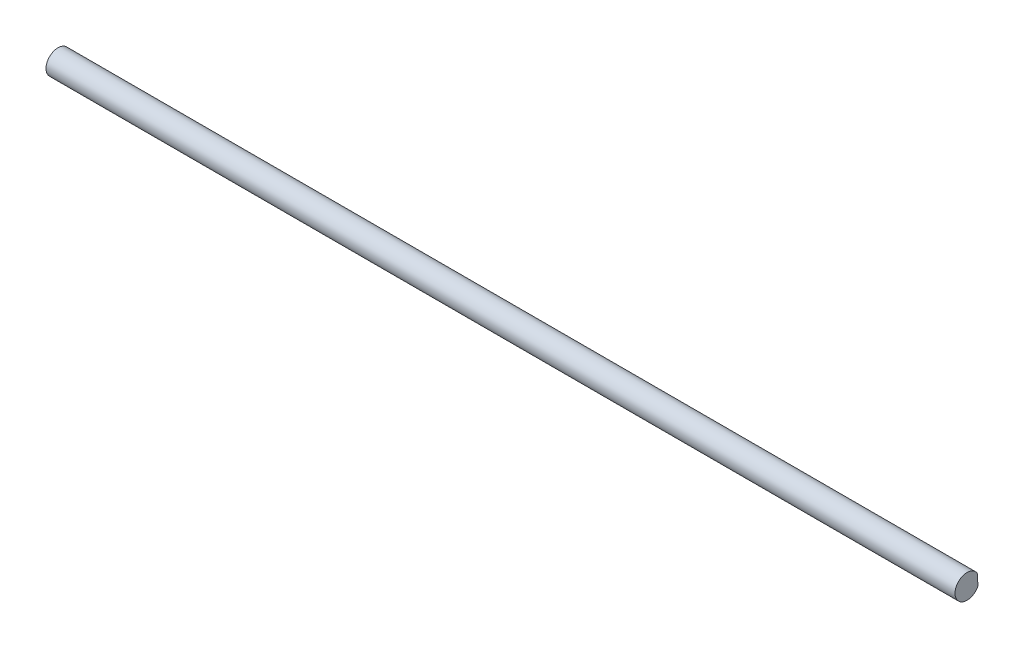
SolidWorks part; units mm, degrees
ref_plane "Plan de face" through (0, 0, 0) normal (0, 0, 1) x (1, 0, 0)
ref_plane "Plan de dessus" through (0, 0, 0) normal (0, 1, 0) x (1, 0, 0)
ref_plane "Plan de droite" through (0, 0, 0) normal (1, 0, 0) x (0, 0, -1)
sketch "Esquisse1" plane through (0, 0, 0) normal (1, 0, 0) x (0, 0, -1)
  line L1 (2.8915, -1.3114) -> (2.6832, 1.6974)
  arc A0 (2.6832, 1.6974) -> (2.8915, -1.3114) centre (0, 0) ccw
  dimension "D1" = 6.35
  dimension "D2" = 2.794
extrude "Boss.-Extru.1" add sketch "Esquisse1" along normal blind 240
